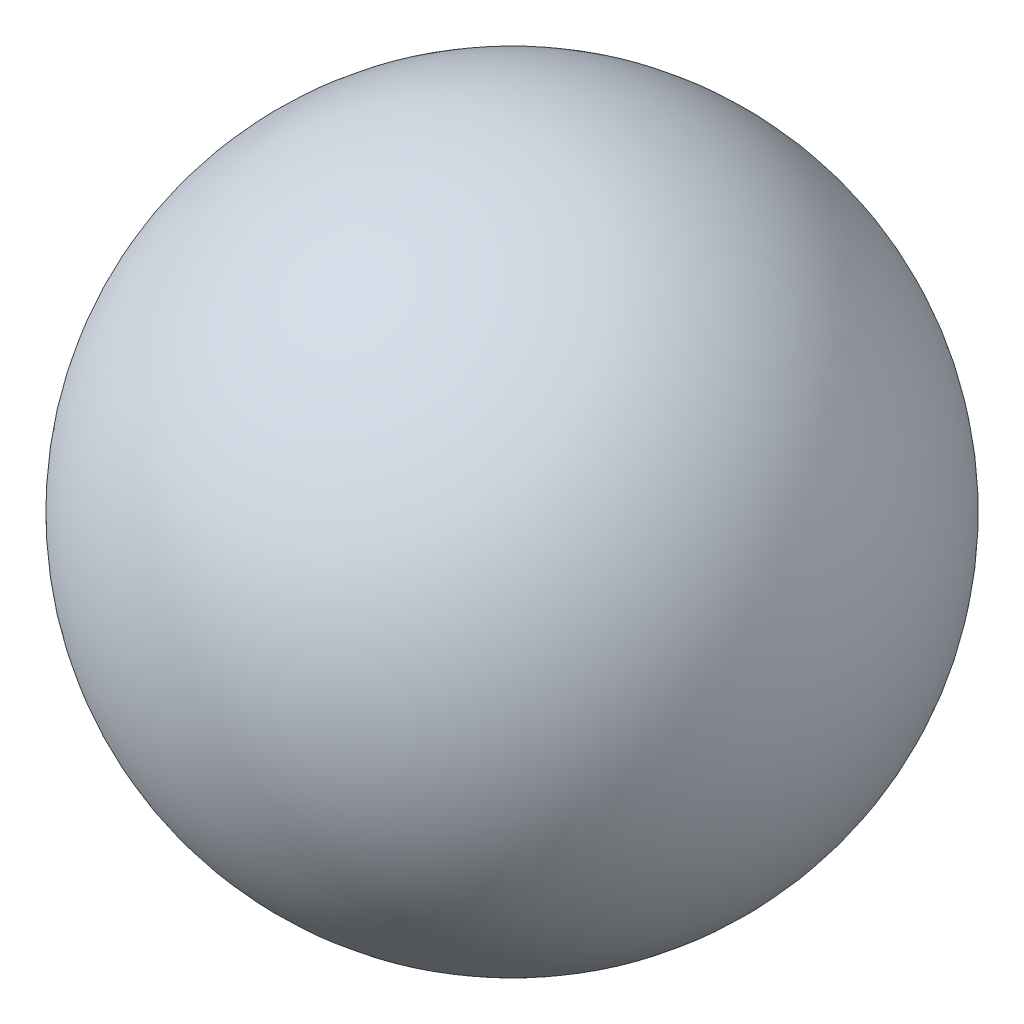
SolidWorks part; units mm, degrees
ref_plane "Front Plane" through (0, 0, 0) normal (0, 0, 1) x (1, 0, 0)
ref_plane "Top Plane" through (0, 0, 0) normal (0, 1, 0) x (1, 0, 0)
ref_plane "Right Plane" through (0, 0, 0) normal (1, 0, 0) x (0, 0, -1)
sketch "Sketch1" plane through (0, 0, 0) normal (0, 0, 1) x (1, 0, 0)
  line L0 (0, 39.8901) -> (0, -38.9272) construction
  line L1 (0, 16) -> (0, -16)
  arc A0 (0, 16) -> (0, -16) centre (0, 0) ccw
  dimension "D1" = 32
revolve "Revolve1" add sketch "Sketch1" angle 360 about L0
sketch "Sketch2" plane through (0, 0, 0) normal (0, 0, 1) x (1, 0, 0)
  line L0 (0, 39.8901) -> (0, -38.9272) construction
  line L1 (0, 15) -> (0, -15)
  arc A0 (0, 15) -> (0, -15) centre (0, 0) ccw
  dimension "D1" = 30
revolve "Cut-Revolve1" cut sketch "Sketch2" angle 360 about L0
sketch "Sketch3" plane through (0, 0, 0) normal (0, 1, 0) x (1, 0, 0)
  circle A0 centre (0, 0) radius 5.25
  dimension "D1" = 10.5
extrude "Cut-Extrude1" [suppressed] cut sketch "Sketch3" along normal through all
